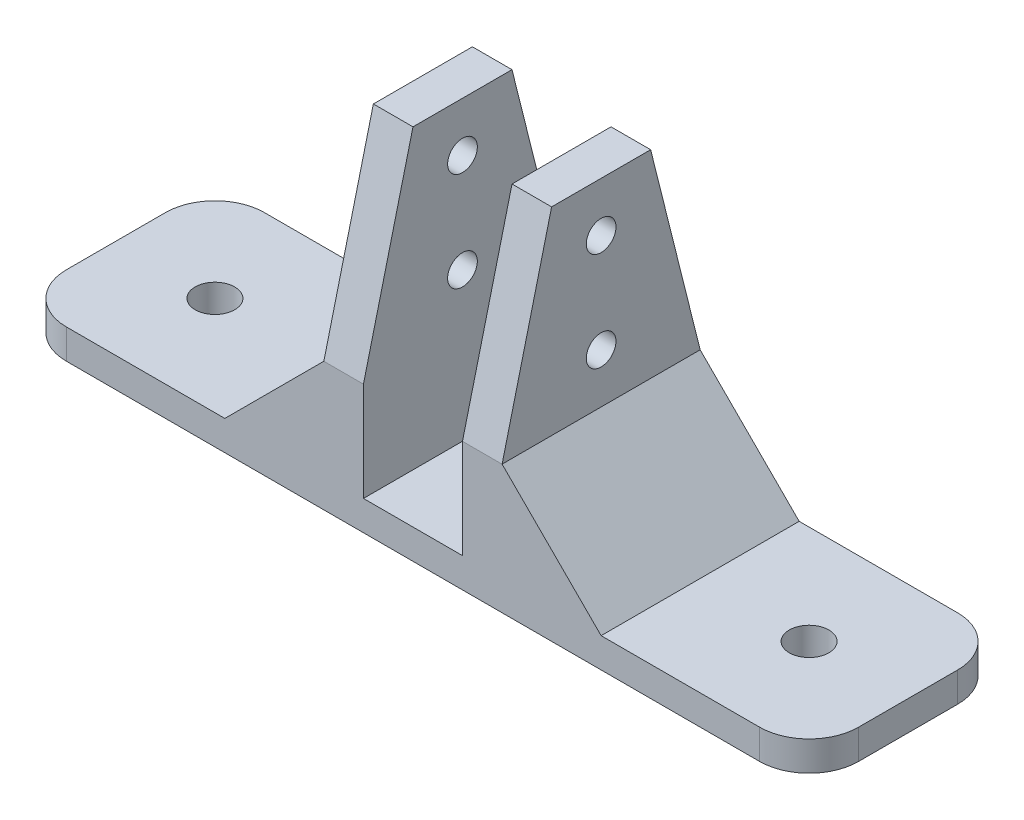
SolidWorks part; units mm, degrees
ref_plane "前视基准面" through (0, 0, 0) normal (0, 0, 1) x (1, 0, 0)
ref_plane "上视基准面" through (0, 0, 0) normal (0, 1, 0) x (1, 0, 0)
ref_plane "右视基准面" through (0, 0, 0) normal (1, 0, 0) x (0, 0, -1)
sketch "草图2" plane through (0, 0, 0) normal (0, 1, 0) x (1, 0, 0)
  line L1 (-40, 10) -> (40, 10)
  line L2 (-40, 10) -> (-40, -10)
  line L3 (-40, -10) -> (40, -10)
  line L4 (40, 10) -> (40, -10)
  line L5 (-40, 10) -> (40, -10) construction
  line L6 (-40, -10) -> (40, 10) construction
  point P0 (0, 0)
extrude "凸台-拉伸1" add sketch "草图2" along normal blind 3
sketch "草图3" plane through (0, 0, 10) normal (0, 0, 1) x (1, 0, 0)
  line L0 (-40, 3) -> (-5, 3)
  line L1 (-40, 3) -> (40, 3) construction
  line L2 (-5, 3) -> (-5, 33)
  line L3 (-5, 33) -> (-9, 33)
  line L4 (-9, 33) -> (-9, 13)
  line L5 (-9, 13) -> (-19, 3)
  line M3 (40, 3) -> (-40, 3)
extrude "凸台-拉伸2" add sketch "草图3" against normal blind 20 contours L4 L5 L2 L3 M3
ref_plane "基准面1" through (0, 0, 0) normal (-1, 0, 0) x (0, 0, 1)
mirror "镜向1" about plane through (0, 0, 0) normal (-1, 0, 0) of "凸台-拉伸2"
hole_wizard "Ø3.0 (3) 直径孔1" positions "草图7" profile "草图4" hole size "Ø3.0" standard "GB" end condition through all
sketch "草图7" plane through (-9, 0, 0) normal (-1, 0, 0) x (0, 0, 1)
  line L0 (0, 28) -> (0, 33)
  line L1 (-10, 33) -> (10, 33) construction
  line L3 (0, 18) -> (0, 13)
  line L4 (-10, 13) -> (10, 13) construction
  point P0 (0, 28)
  point P2 (0, 18)
sketch "草图4" plane through (-9, 28, 0) normal (0, 1, 0) x (0, 0, 1)
  line L0 (0, 0) -> (0, 49)
  line L1 (0, 49) -> (1.5, 49)
  line L2 (1.5, 49) -> (1.5, 0)
  line L5 (1.5, 0) -> (0, 0)
  line L11 (0, -6.35) -> (0, 107.95) construction
  dimension "通孔孔直径" = 3
  dimension "通孔孔深度" = 49
hole_wizard "Ø4.0 (4) 直径孔1" positions "草图9" profile "草图8" hole size "Ø4.0" standard "GB" end condition through all
sketch "草图9" plane through (0, 3, 0) normal (0, 1, 0) x (1, 0, 0)
  line L0 (-30, 0) -> (-40, 0)
  line L1 (-40, 10) -> (-40, -10) construction
  line L3 (30, 0) -> (40, 0)
  line L4 (40, -10) -> (40, 10) construction
  point P0 (-30, 0)
  point P2 (30, 0)
sketch "草图8" plane through (-30, 3, 0) normal (1, 0, 0) x (0, 0, 1)
  line L0 (0, 0) -> (0, 3)
  line L1 (0, 3) -> (2, 3)
  line L2 (2, 3) -> (2, 0)
  line L5 (2, 0) -> (0, 0)
  line L11 (0, -6.35) -> (0, 107.95) construction
  dimension "通孔孔直径" = 4
  dimension "通孔孔深度" = 3
sketch "草图10" plane through (-9, 0, 0) normal (-1, 0, 0) x (0, 0, 1)
  line L0 (10, 13) -> (10, 33)
  line L1 (10, 33) -> (5, 33)
  line L2 (-10, 33) -> (10, 33) construction
  line L3 (5, 33) -> (10, 13)
  line L4 (-10, 13) -> (-10, 33)
  line L5 (-10, 33) -> (-5, 33)
  line L6 (-5, 33) -> (-10, 13)
extrude "切除-拉伸1" cut sketch "草图10" against normal blind 200
fillet "圆角1" radius 5 4 edges at (40, 1.5, -10) (40, 1.5, 10) (-40, 1.5, 10) (-40, 1.5, -10)
